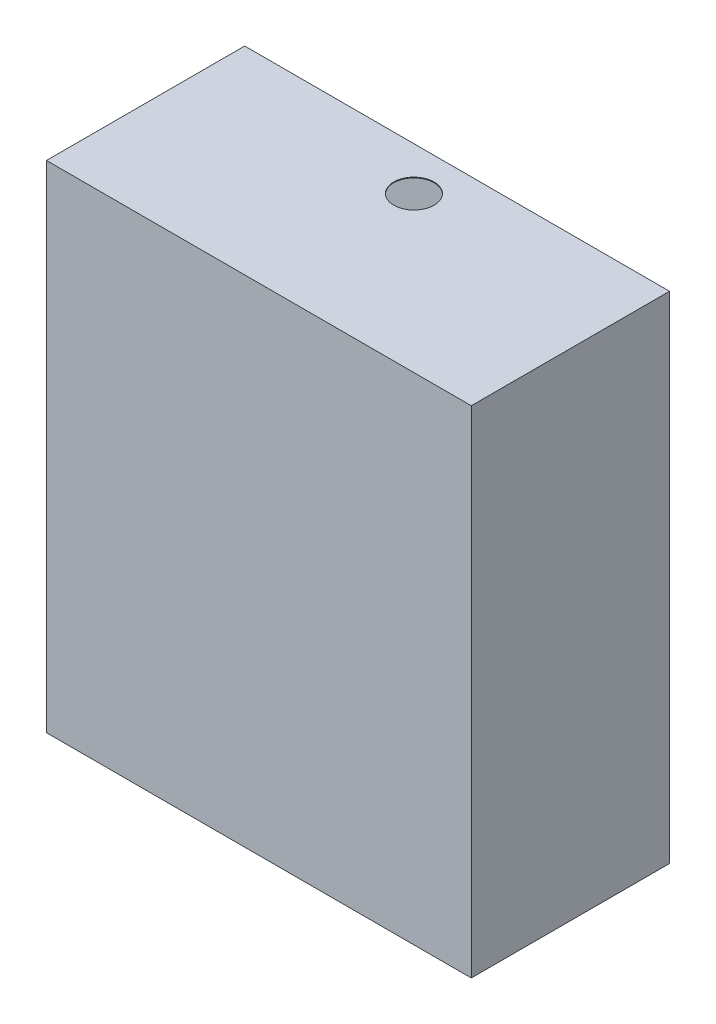
SolidWorks part; units mm, degrees
material "Q235"
ref_plane "前视" through (0, 0, 0) normal (0, 0, 1) x (1, 0, 0)
ref_plane "上视" through (0, 0, 0) normal (0, 1, 0) x (1, 0, 0)
ref_plane "右视" through (0, 0, 0) normal (1, 0, 0) x (0, 0, -1)
sketch "草图1" plane through (0, 0, 0) normal (0, 0, 1) x (1, 0, 0)
  line L1 (-300, -350) -> (300, -350)
  line L2 (-300, -350) -> (-300, 350)
  line L3 (-300, 350) -> (300, 350)
  line L4 (300, -350) -> (300, 350)
  line L5 (-300, -350) -> (300, 350) construction
  line L6 (-300, 350) -> (300, -350) construction
  point P0 (0, 0)
  dimension "D1" = 600
  dimension "D2" = 700
extrude "凸台-拉伸1" add sketch "草图1" along normal mid plane 280
shell "抽壳1" thickness 1
hole_wizard "孔1" positions "草图3" profile "草图2" legacy end condition up to next
sketch "草图3" plane through (0, 350, 0) normal (0, 1, 0) x (1, 0, 0)
  line L0 (0, -140) -> (0, 79) construction
  line L1 (300, -140) -> (-300, -140) construction
  line L2 (299, 139) -> (-299, 139) construction
  point P0 (0, 79)
  dimension "D1" = 60
sketch "草图2" plane through (0, 350, -79) normal (1, 0, 0) x (0, 0, 1)
  line L0 (0, 0) -> (0, 1)
  line L1 (0, 1) -> (28.5, 1)
  line L2 (28.5, 1) -> (28.5, 0)
  line L3 (28.5, 0) -> (0, 0)
  line L4 (0, 110) -> (0, -10) construction
  dimension "直径" = 57
  dimension "深度" = 1
